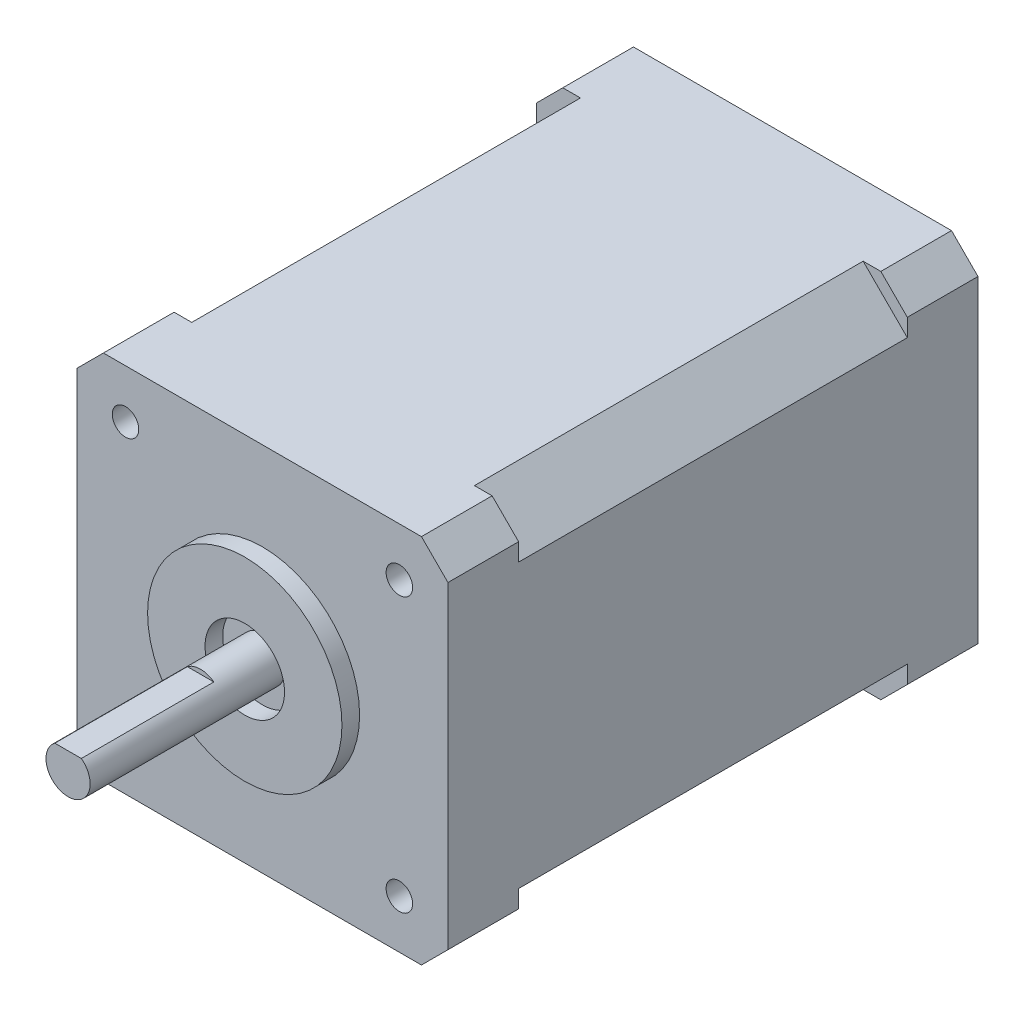
SolidWorks part; units mm, degrees
ref_plane "Alzado" through (0, 0, 0) normal (0, 0, 1) x (1, 0, 0)
ref_plane "Planta" through (0, 0, 0) normal (0, 1, 0) x (1, 0, 0)
ref_plane "Vista lateral" through (0, 0, 0) normal (1, 0, 0) x (0, 0, -1)
sketch "Croquis1" plane through (0, 0, 0) normal (0, 0, 1) x (1, 0, 0)
  line L0 (-21, 16) -> (-16, 21)
  line L1 (-16, -21) -> (16, -21)
  line L2 (-21, -16) -> (-21, 16)
  line L3 (-16, 21) -> (16, 21)
  line L4 (21, -16) -> (21, 16)
  line L5 (-21, -21) -> (21, 21) construction
  line L6 (-21, 21) -> (21, -21) construction
  line L7 (16, 21) -> (21, 16)
  line L8 (16, -21) -> (21, -16)
  line L9 (-21, -16) -> (-16, -21)
  point P0 (0, 0)
  dimension "D1" = 42
  dimension "D2" = 42
extrude "Saliente-Extruir1" add sketch "Croquis1" along normal blind 44
sketch "Croquis2" plane through (0, 0, 44) normal (0, 0, 1) x (1, 0, 0)
  line L0 (-21, 18) -> (-18, 21)
  line L1 (-18, -21) -> (18, -21)
  line L2 (-21, -18) -> (-21, 18)
  line L3 (-18, 21) -> (18, 21)
  line L4 (21, -18) -> (21, 18)
  line L5 (-21, -21) -> (21, 21) construction
  line L6 (-21, 21) -> (21, -21) construction
  line L7 (18, 21) -> (21, 18)
  line L8 (18, -21) -> (21, -18)
  line L9 (-21, -18) -> (-18, -21)
  point P0 (0, 0)
  dimension "D1" = 42
  dimension "D2" = 42
extrude "Saliente-Extruir2" add sketch "Croquis2" along normal blind 8
sketch "Croquis3" plane through (0, 0, 0) normal (0, 0, -1) x (-1, 0, 0)
  line L0 (-21, 18) -> (-18, 21)
  line L1 (-18, -21) -> (18, -21)
  line L2 (-21, -18) -> (-21, 18)
  line L3 (-18, 21) -> (18, 21)
  line L4 (21, -18) -> (21, 18)
  line L5 (-21, -21) -> (21, 21) construction
  line L6 (-21, 21) -> (21, -21) construction
  line L7 (18, 21) -> (21, 18)
  line L8 (18, -21) -> (21, -18)
  line L9 (-21, -18) -> (-18, -21)
  point P0 (0, 0)
  dimension "D1" = 42
  dimension "D2" = 42
extrude "Saliente-Extruir3" add sketch "Croquis3" along normal blind 8
sketch "Croquis4" plane through (0, 0, 52) normal (0, 0, 1) x (1, 0, 0)
  line L0 (0, 21) -> (0, -21) construction
  line L1 (18, 21) -> (-18, 21) construction
  line L2 (-18, -21) -> (18, -21) construction
  line L3 (-21, 0) -> (21, 0) construction
  line L4 (-21, 18) -> (-21, -18) construction
  line L5 (21, -18) -> (21, 18) construction
  circle A0 centre (0, 0) radius 11
  circle A1 centre (0, 0) radius 4.5
  dimension "D1" = 22
  dimension "D2" = 9
extrude "Saliente-Extruir4" add sketch "Croquis4" along normal blind 2
sketch "Croquis5" plane through (0, 0, 52) normal (0, 0, 1) x (1, 0, 0)
  circle A0 centre (0, 0) radius 2.5
  dimension "D1" = 5
extrude "Saliente-Extruir5" add sketch "Croquis5" along normal blind 22
sketch "Croquis6" plane through (0, 0, 74) normal (0, 0, 1) x (1, 0, 0)
  line L0 (-1.5, 2) -> (1.5, 2)
  arc A0 (1.5, 2) -> (-1.5, 2) centre (0, 0) ccw
  dimension "D1" = 2.5
  dimension "D2" = 3
extrude "Cortar-Extruir1" cut sketch "Croquis6" against normal blind 15
sketch "Croquis7" plane through (0, 0, 52) normal (0, 0, 1) x (1, 0, 0)
  line L3 (-15.5, -15.5) -> (15.5, -15.5) construction
  line L4 (-15.5, -15.5) -> (-15.5, 15.5) construction
  line L5 (-15.5, 15.5) -> (15.5, 15.5) construction
  line L6 (15.5, -15.5) -> (15.5, 15.5) construction
  line L7 (-15.5, -15.5) -> (15.5, 15.5) construction
  line L8 (-15.5, 15.5) -> (15.5, -15.5) construction
  circle A0 centre (-15.5, 15.5) radius 1.5
  circle A1 centre (15.5, 15.5) radius 1.5
  circle A2 centre (15.5, -15.5) radius 1.5
  circle A3 centre (-15.5, -15.5) radius 1.5
  point P0 (0, 0)
  dimension "D3" = 3
  dimension "D1" = 31
  dimension "D2" = 31
extrude "Cortar-Extruir2" cut sketch "Croquis7" against normal blind 4
sketch "Croquis8" plane through (0, 0, 52) normal (0, 0, 1) x (1, 0, 0)
  line L0 (18, 21) -> (-18, 21) construction
  line L1 (-27, -30.52) -> (98, -30.52)
  line L2 (-27, -30.52) -> (-27, 22)
  line L3 (-27, 22) -> (27, 22)
  line L4 (27, 0) -> (84.8426, 0) construction
  line L5 (-21, 18) -> (-21, -18) construction
  line L6 (27, -14.52) -> (27, -30.52) construction
  line L7 (-18, -21) -> (18, -21) construction
  line L8 (-27, -25.76) -> (98, -25.76) construction
  line L9 (0, -25.76) -> (0, -30.52) construction
  line L10 (0, -25.76) -> (0, 22) construction
  line L11 (0, 0) -> (27, 0) construction
  line L12 (0, 0) -> (-27, 0) construction
  line L13 (62.5, -14.52) -> (62.5, -30.52) construction
  line L14 (65, 49.48) -> (140.3741, 49.48) construction
  line L15 (72, -25.76) -> (90, -25.76) construction
  line L16 (72, -23.26) -> (90, -23.26)
  line L17 (72, -28.26) -> (90, -28.26)
  line L18 (21, -18) -> (21, 18) construction
  line L19 (27, -14.52) -> (27, 22)
  line L20 (53, -25.76) -> (35, -25.76) construction
  line L21 (65, 38.6756) -> (65, -5.2541) construction
  line L22 (27, -14.52) -> (98, -14.52)
  line L23 (98, -30.52) -> (98, -14.52)
  line L24 (53, -23.26) -> (35, -23.26)
  line L25 (53, -28.26) -> (35, -28.26)
  circle A0 centre (-15.5, 15.5) radius 1.75
  arc A1 (72, -23.26) -> (72, -28.26) centre (72, -25.76) ccw
  arc A2 (90, -28.26) -> (90, -23.26) centre (90, -25.76) ccw
  circle A3 centre (15.5, 15.5) radius 1.75
  circle A4 centre (15.5, -15.5) radius 1.75
  circle A5 centre (-15.5, -15.5) radius 1.75
  arc A6 (53, -23.26) -> (53, -28.26) centre (53, -25.76) cw
  arc A7 (35, -28.26) -> (35, -23.26) centre (35, -25.76) cw
  circle A8 centre (0, 0) radius 12
  circle A9 centre (65, 19.48) radius 30 construction
  point P39 (81, -25.76)
  point P55 (44, -25.76)
  dimension "D1" = 3.5
  dimension "D2" = 1
  dimension "D4" = 24
  dimension "D12" = 60
  dimension "D9" = 50
  dimension "D11" = 65
  dimension "D15" = 8
  dimension "D16" = 35.5
  dimension "D3" = 6
  dimension "D5" = 9.52
  dimension "D6" = 4.76
  dimension "D7" = 54
  dimension "D8" = 52.52
  dimension "D10" = 16
  dimension "D13" = 125
  dimension "D14" = 5
  dimension "D17" = 6
  dimension "D18" = 18
  dimension "D19" = 80
